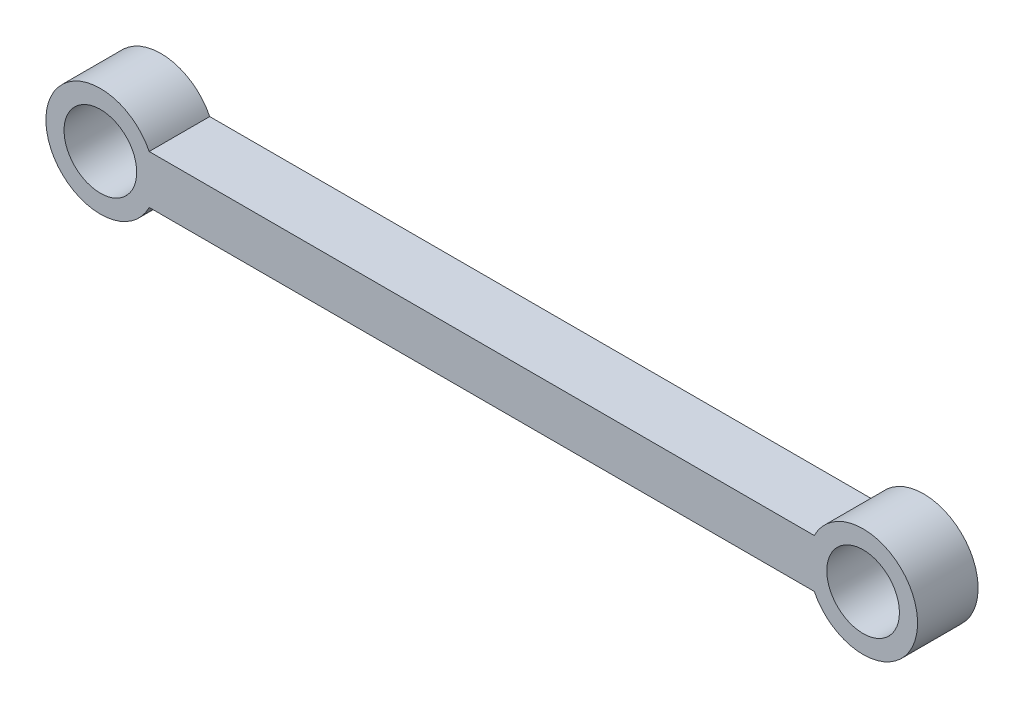
SolidWorks part; units mm, degrees
ref_plane "Front Plane" through (0, 0, 0) normal (0, 0, 1) x (1, 0, 0)
ref_plane "Top Plane" through (0, 0, 0) normal (0, 1, 0) x (1, 0, 0)
ref_plane "Right Plane" through (0, 0, 0) normal (1, 0, 0) x (0, 0, -1)
sketch "Sketch1" plane through (0, 0, 0) normal (0, 0, 1) x (1, 0, 0)
  line L0 (0, 0) -> (80.01, 0) construction
  line L1 (5.715, 0) -> (5.715, 2.54) construction
  line L2 (5.715, 2.54) -> (5.715, -2.54) construction
  line L3 (5.1195, 2.54) -> (74.8905, 2.54)
  line L4 (5.1195, -2.54) -> (74.8905, -2.54)
  circle A0 centre (0, 0) radius 3.81
  circle A1 centre (80.01, 0) radius 3.81
  arc A2 (5.1195, 2.54) -> (5.1195, -2.54) centre (0, 0) ccw
  arc A3 (74.8905, -2.54) -> (74.8905, 2.54) centre (80.01, 0) ccw
  dimension "D2" = 7.62
  dimension "D1" = 80.01
extrude "Boss-Extrude1" add sketch "Sketch1" along normal blind 6.35
